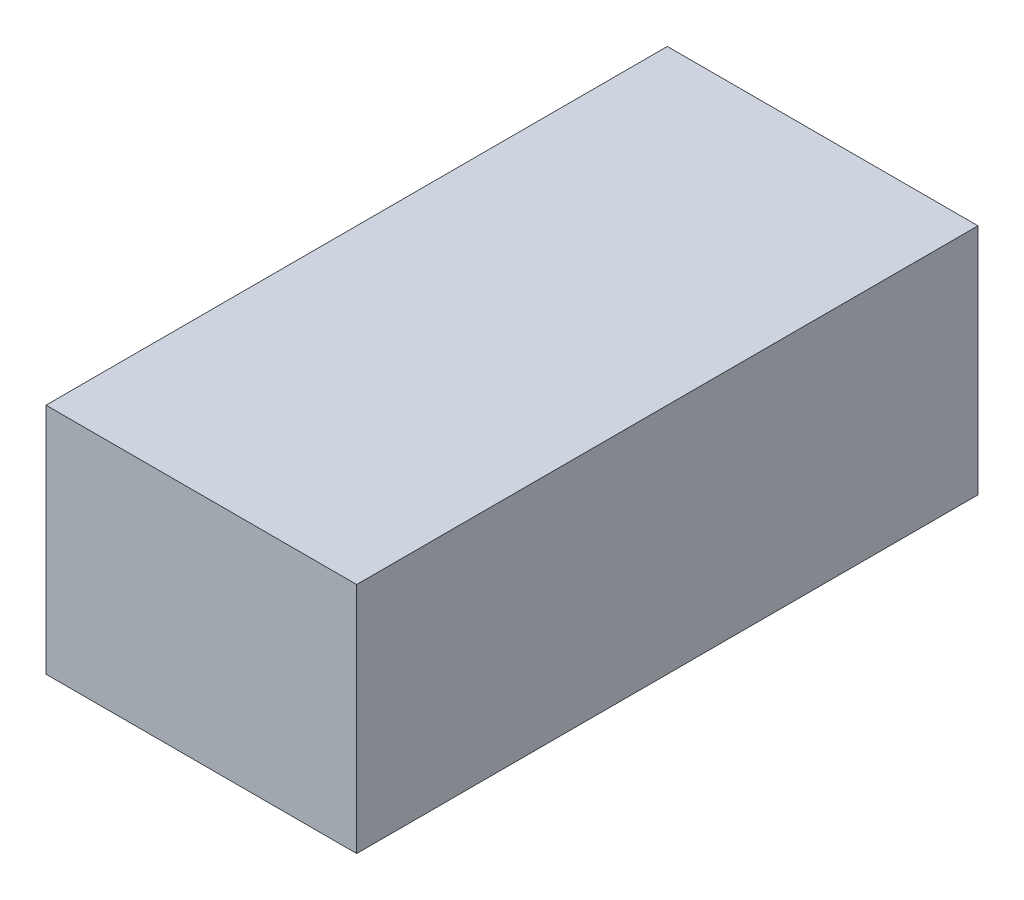
SolidWorks part; units mm, degrees
ref_plane "Front" through (0, 0, 0) normal (0, 0, 1) x (1, 0, 0)
ref_plane "Top" through (0, 0, 0) normal (0, 1, 0) x (1, 0, 0)
ref_plane "Right" through (0, 0, 0) normal (1, 0, 0) x (0, 0, -1)
sketch "Sketch1" plane through (0, 0, 0) normal (0, 1, 0) x (1, 0, 0)
  line L1 (-12.7, -25.4) -> (12.7, -25.4)
  line L2 (-12.7, -25.4) -> (-12.7, 25.4)
  line L3 (-12.7, 25.4) -> (12.7, 25.4)
  line L4 (12.7, -25.4) -> (12.7, 25.4)
  line L5 (-12.7, -25.4) -> (12.7, 25.4) construction
  line L6 (-12.7, 25.4) -> (12.7, -25.4) construction
  point P0 (0, 0)
  dimension "D1" = 25.4
  dimension "D2" = 50.8
extrude "Boss-Extrude1" add sketch "Sketch1" along normal blind 19.05
